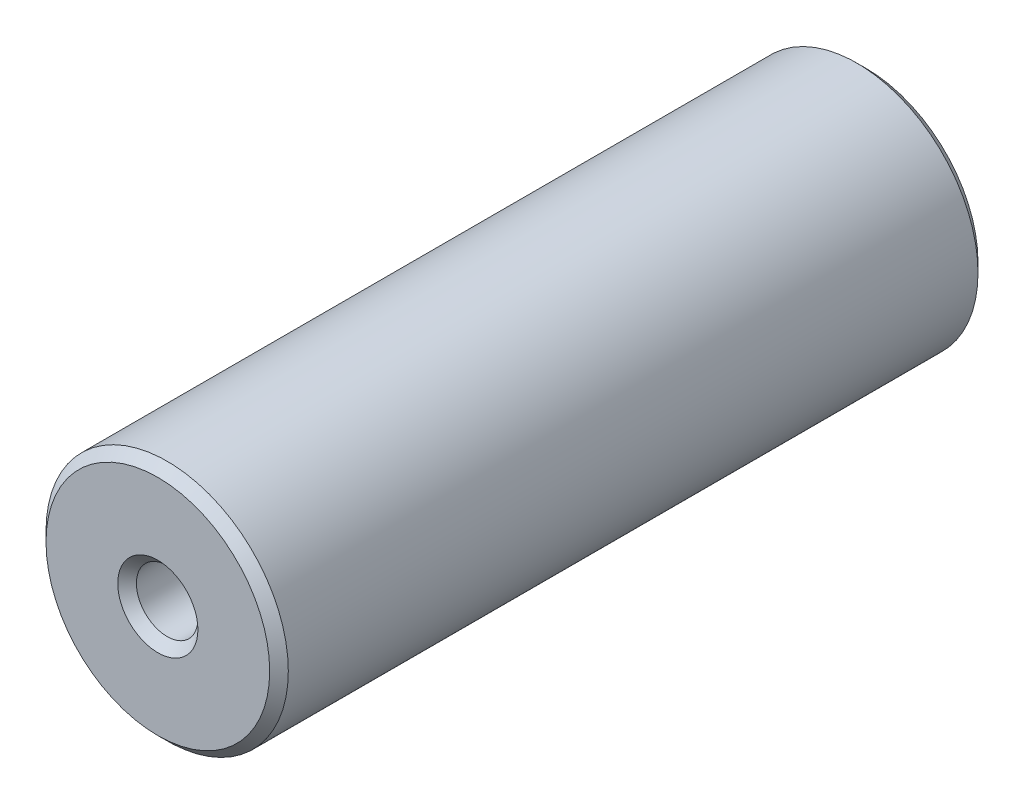
SolidWorks part; units mm, degrees
ref_plane "Plan de face" through (0, 0, 0) normal (0, 0, 1) x (1, 0, 0)
ref_plane "Plan de dessus" through (0, 0, 0) normal (0, 1, 0) x (1, 0, 0)
ref_plane "Plan de droite" through (0, 0, 0) normal (1, 0, 0) x (0, 0, -1)
sketch "Esquisse1" plane through (0, 0, 0) normal (0, 0, 1) x (1, 0, 0)
  circle A0 centre (0, 0) radius 3.3
  circle A1 centre (0, 0) radius 13
  dimension "D2" = 26
extrude "Boss.-Extru.1" add sketch "Esquisse1" along normal blind 76
chamfer "Chanfrein1" distance 1 angle 45 4 edges at (3.3, 0, 0) (3.3, 0, 76) (13, 0, 0) (13, 0, 76)
